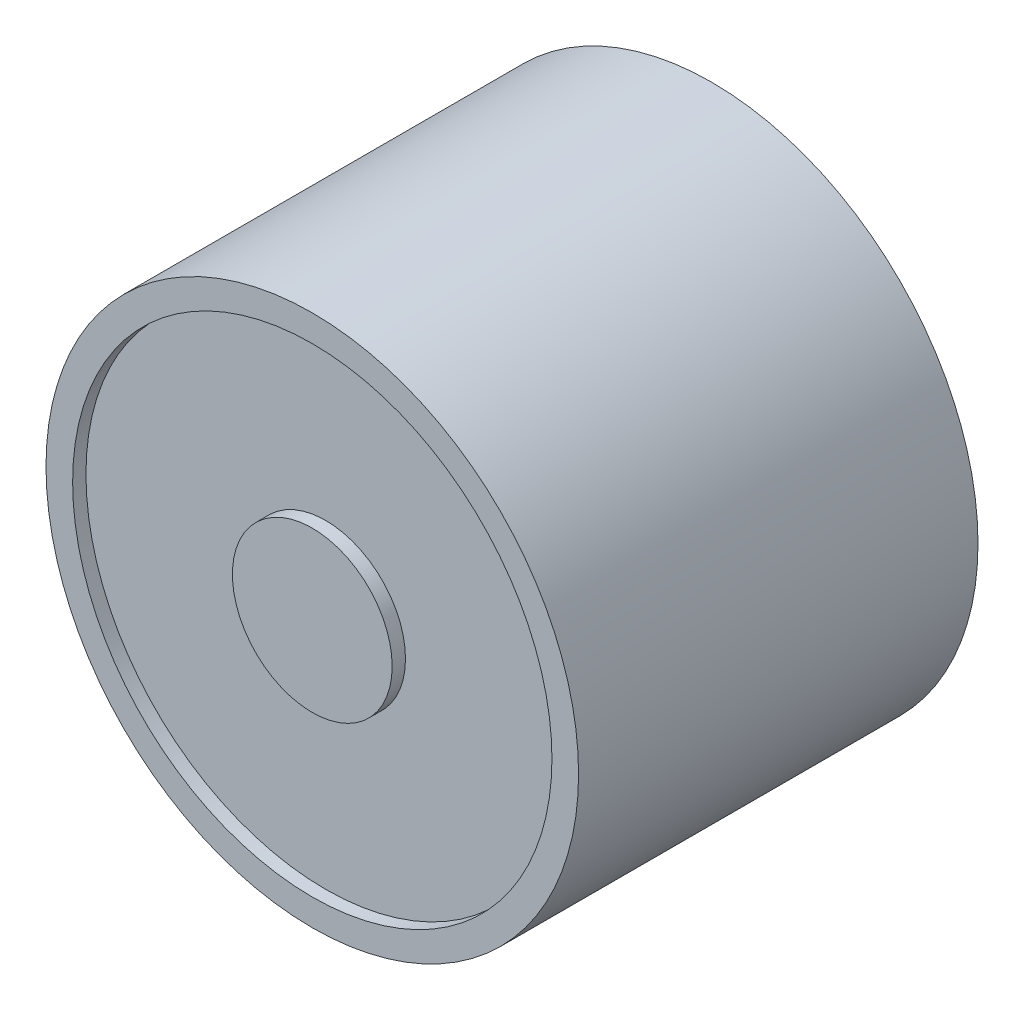
SolidWorks part; units mm, degrees
ref_plane "Ön Düzlem" through (0, 0, 0) normal (0, 0, 1) x (1, 0, 0)
ref_plane "Üst Düzlem" through (0, 0, 0) normal (0, 1, 0) x (1, 0, 0)
ref_plane "Sağ Düzlem" through (0, 0, 0) normal (1, 0, 0) x (0, 0, -1)
sketch "Sketch1" plane through (0, 0, 0) normal (0, 0, 1) x (1, 0, 0)
  circle A0 centre (0, 0) radius 10
  dimension "D1" = 20
extrude "Boss-Extrude1" add sketch "Sketch1" along normal blind 15
sketch "Sketch2" plane through (0, 0, 15) normal (0, 0, 1) x (1, 0, 0)
  circle A0 centre (0, 0) radius 9
  circle A1 centre (0, 0) radius 3
  dimension "D1" = 18
  dimension "D2" = 6
extrude "Cut-Extrude1" cut sketch "Sketch2" against normal blind 0.5
sketch "Sketch3" plane through (0, 0, 0) normal (0, 0, -1) x (-1, 0, 0)
  circle A0 centre (0, 0) radius 2
  dimension "D1" = 4
extrude "Cut-Extrude2" cut sketch "Sketch3" against normal blind 3
